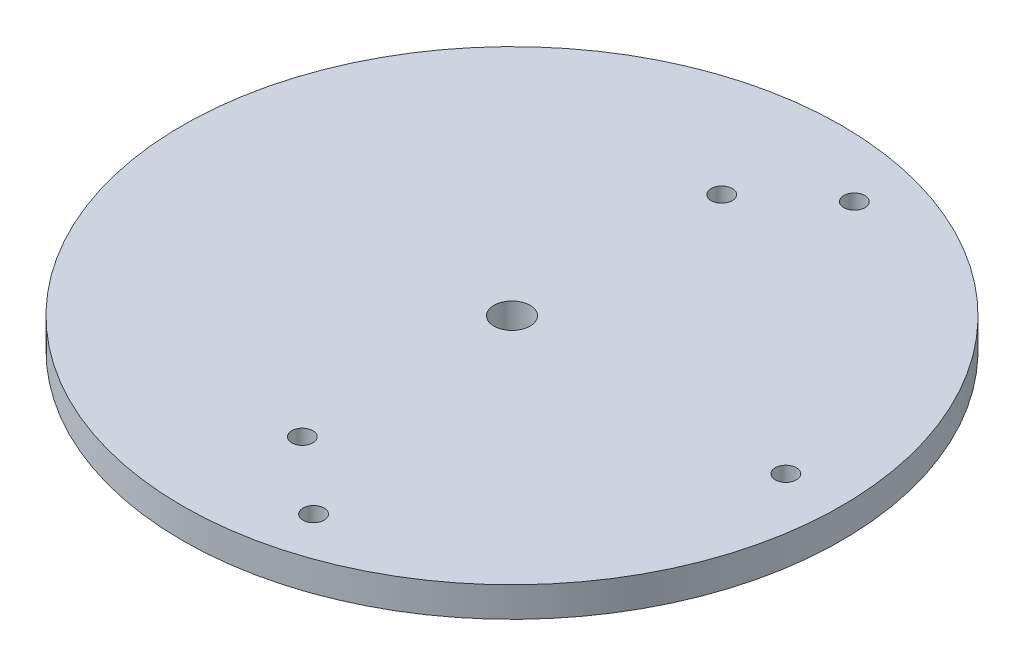
SolidWorks part; units mm, degrees
ref_plane "Front Plane" through (0, 0, 0) normal (0, 0, 1) x (1, 0, 0)
ref_plane "Top Plane" through (0, 0, 0) normal (0, 1, 0) x (1, 0, 0)
ref_plane "Right Plane" through (0, 0, 0) normal (1, 0, 0) x (0, 0, -1)
sketch "Sketch1" plane through (0, 0, 0) normal (0, 1, 0) x (1, 0, 0)
  circle A0 centre (-16.0725, 12.0544) radius 69.85
  dimension "D1" = 139.7
extrude "Boss-Extrude1" add sketch "Sketch1" along normal blind 6.35
sketch "Sketch5" plane through (0, 6.35, 0) normal (0, 1, 0) x (1, 0, 0)
  line L0 (-85.9225, 12.0544) -> (-19.8984, 12.0544) construction
  line L1 (-16.0725, 55.9942) -> (-16.0725, 15.8803) construction
  line L2 (-12.2466, 12.0544) -> (39.7281, 12.0544) construction
  line L3 (-16.0725, 8.2285) -> (-16.0725, -30.1572) construction
  line L4 (-16.0725, -34.634) -> (-16.0725, -57.7956) construction
  line L5 (-16.0725, 12.0544) -> (-1.3181, 67.1186) construction
  line L6 (-16.0725, 12.0544) -> (-1.259, -43.2305) construction
  line L7 (44.2049, 12.0544) -> (53.7775, 12.0544) construction
  circle A0 centre (-16.0725, 56.5044) radius 2.2384
  circle A1 centre (-16.0725, 12.0544) radius 69.85 construction
  circle A2 centre (-16.0725, -32.3956) radius 2.2384
  circle A3 centre (-16.0725, 12.0544) radius 3.8259
  circle A4 centre (-16.0725, 12.0544) radius 51.689
  circle A5 centre (41.9665, 12.0544) radius 2.2384
  circle A6 centre (-0.7388, 69.2807) radius 2.2384
  circle A7 centre (-0.6796, -45.3926) radius 2.2384
  dimension "D1" = 4.4768
  dimension "D2" = 4.4768
  dimension "D5" = 7.6518
  dimension "D6" = 103.378
  dimension "D8" = 4.4768
  dimension "D9" = 4.4768
  dimension "D10" = 4.4768
  dimension "D3" = 88.9
  dimension "D4" = 44.45
  dimension "D7" = 58.039
  dimension "D11" = 75
  dimension "D12" = 75
extrude "Cut-Extrude3" cut sketch "Sketch5" against normal blind 12.7 contours A6 | A0 | A3 | A2 | A7 | A5
equation "\"hole_diameter\"= 5 / 32"
equation "\"tolerance\"= 0.02"
equation "\"D1@Sketch5\"=\"hole_diameter\"+\"tolerance\""
equation "\"D2@Sketch5\"=\"hole_diameter\"+\"tolerance\""
equation "\"D5@Sketch5\"=9/32+\"tolerance\""
equation "\"lidar_diameter\"= 4.07"
equation "\"D6@Sketch5\"=\"lidar_diameter\""
equation "\"D7@Sketch5\"=(\"lidar_diameter\"/2)+0.25"
equation "\"D8@Sketch5\"=\"hole_diameter\"+\"tolerance\""
equation "\"D9@Sketch5\"=\"hole_diameter\"+\"tolerance\""
equation "\"D10@Sketch5\"=\"hole_diameter\"+\"tolerance\""
